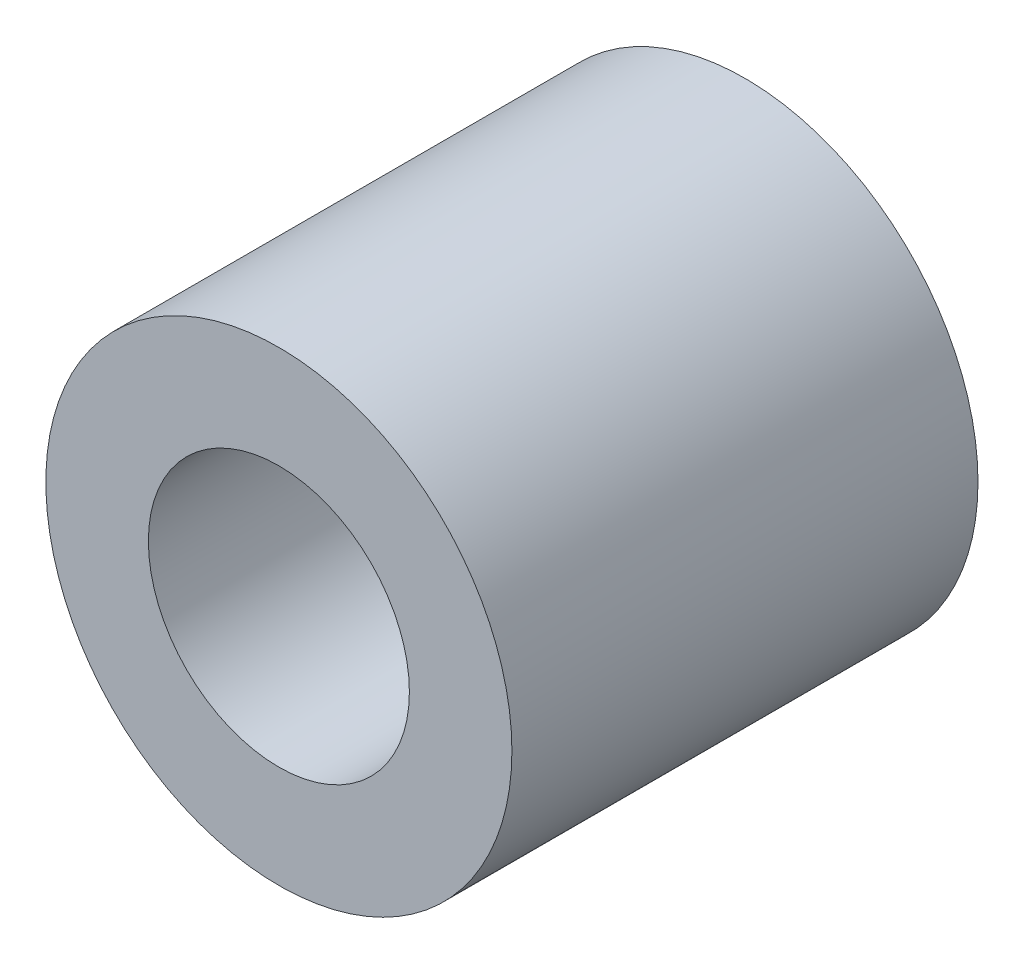
SolidWorks part; units mm, degrees
ref_plane "Front Plane" through (0, 0, 0) normal (0, 0, 1) x (1, 0, 0)
ref_plane "Top Plane" through (0, 0, 0) normal (0, 1, 0) x (1, 0, 0)
ref_plane "Right Plane" through (0, 0, 0) normal (1, 0, 0) x (0, 0, -1)
sketch "Sketch1" plane through (0, 0, 0) normal (0, 0, 1) x (1, 0, 0)
  circle A0 centre (0, 0) radius 3.175
  circle A1 centre (0, 0) radius 1.778
  dimension "OD" = 6.35
  dimension "ID" = 3.556
extrude "Extrude1" add sketch "Sketch1" along normal mid plane 6.35
sketch "Sketch2" plane through (0, 0, 0) normal (1, 0, 0) x (0, 0, -1)
  line L0 (-3.175, -1.778) -> (3.175, -1.778) construction
  line L3 (3.175, 1.778) -> (-3.175, 1.778) construction
  line L5 (-3.175, -1.778) -> (3.175, -1.778)
  line L6 (3.175, 1.778) -> (-3.175, 1.778)
sketch "Sketch4" plane through (0, 0, 3.175) normal (0, 0, 1) x (1, 0, 0)
  line L0 (0, 0) -> (-1.2572, 1.2572)
  line L1 (0, -3.4925) -> (0, 3.4925) construction
  circle A0 centre (0, 0) radius 1.778 construction
  dimension "D1" = 45
